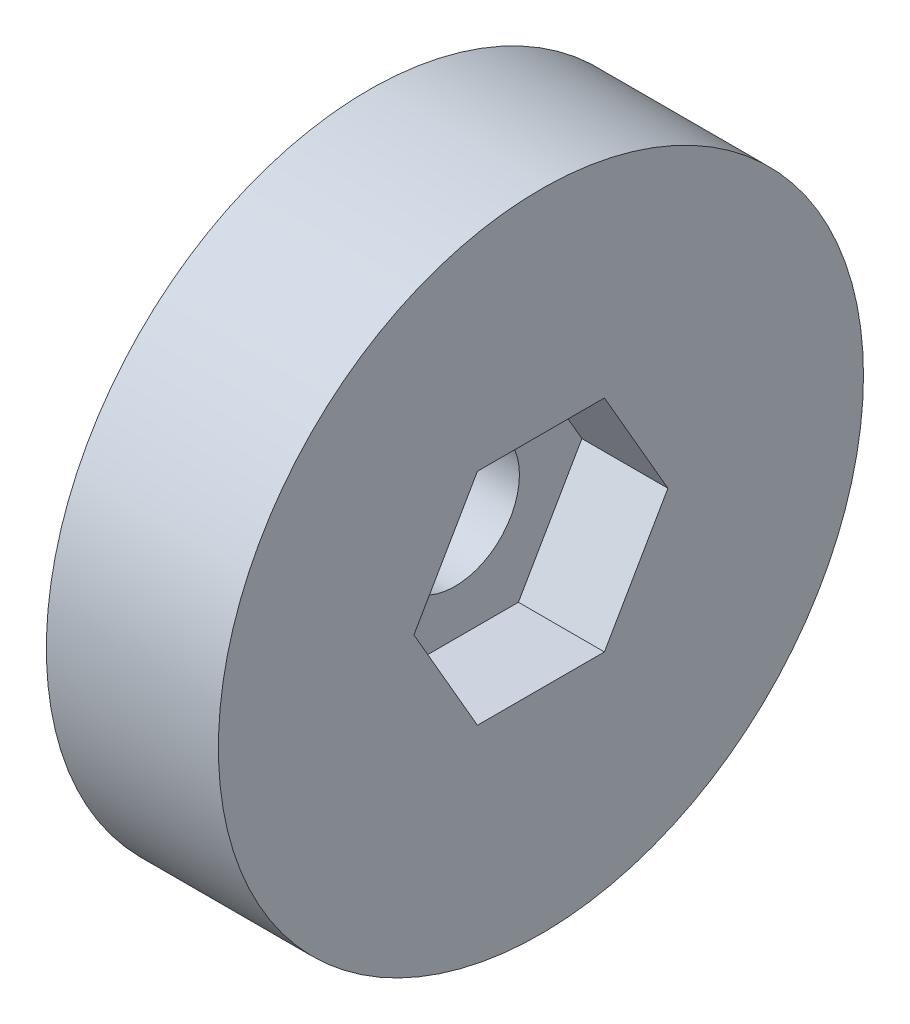
SolidWorks part; units mm, degrees
ref_plane "Front Plane" through (0, 0, 0) normal (0, 0, 1) x (1, 0, 0)
ref_plane "Top Plane" through (0, 0, 0) normal (0, 1, 0) x (1, 0, 0)
ref_plane "Right Plane" through (0, 0, 0) normal (1, 0, 0) x (0, 0, -1)
sketch "Sketch1" plane through (0, 0, 0) normal (1, 0, 0) x (0, 0, -1)
  circle A0 centre (0, 0) radius 19.05
  circle A1 centre (0, 0) radius 3.81
  dimension "D1" = 38.1
  dimension "D2" = 7.62
extrude "Boss-Extrude1" add sketch "Sketch1" along normal blind 5.08
sketch "Sketch2" plane through (5.08, 0, 0) normal (1, 0, 0) x (0, 0, -1)
  line L1 (7.5, 0) -> (3.75, 6.4952)
  line L2 (3.75, 6.4952) -> (-3.75, 6.4952)
  line L3 (-3.75, 6.4952) -> (-7.5, 0)
  line L4 (-7.5, 0) -> (-3.75, -6.4952)
  line L5 (-3.75, -6.4952) -> (3.75, -6.4952)
  line L6 (3.75, -6.4952) -> (7.5, 0)
  circle A0 centre (0, 0) radius 19.05 construction
  circle A1 centre (0, 0) radius 19.05
  circle A2 centre (0, 0) radius 6.4952 construction
  dimension "D1" = 15
extrude "Boss-Extrude2" add sketch "Sketch2" along normal blind 5.08
